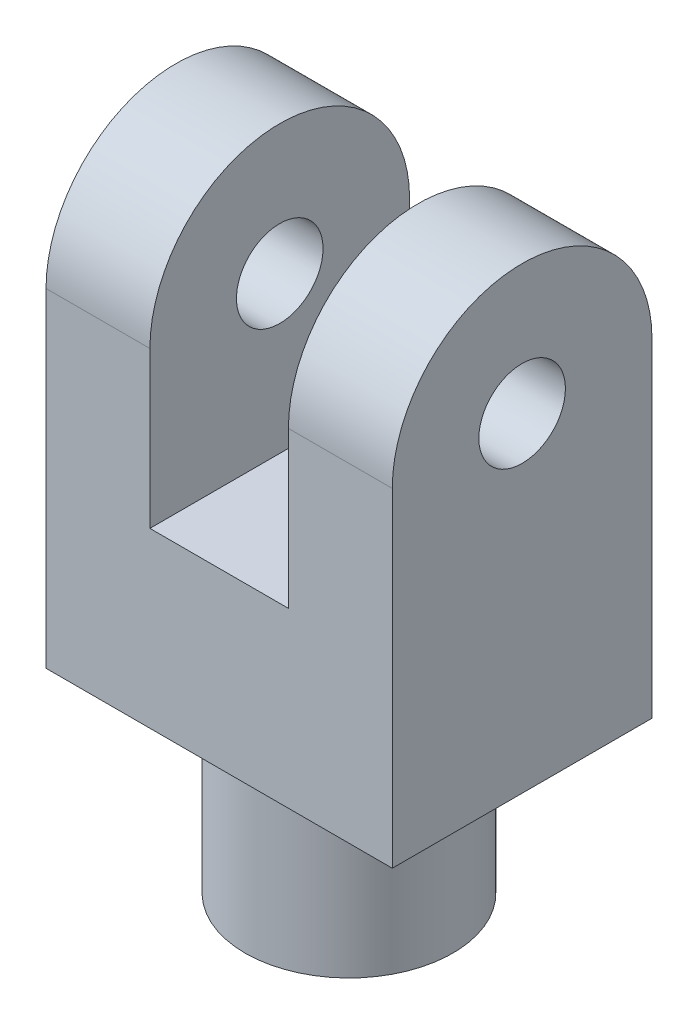
SolidWorks part; units mm, degrees
ref_plane "前视基准面" through (0, 0, 0) normal (0, 0, 1) x (1, 0, 0)
ref_plane "上视基准面" through (0, 0, 0) normal (0, 1, 0) x (1, 0, 0)
ref_plane "右视基准面" through (0, 0, 0) normal (1, 0, 0) x (0, 0, -1)
ref_plane "基准面1" through (-20, 0, 0) normal (1, 0, 0) x (0, 0, -1)
sketch "草图1" plane through (-20, 0, 0) normal (1, 0, 0) x (0, 0, -1)
  line L0 (15, 20) -> (-15, 20)
  line L1 (-15, 20) -> (-15, 58)
  line L2 (15, 58) -> (15, 20)
  arc A0 (-15, 58) -> (15, 58) centre (0, 58) cw
extrude "凸台-拉伸1" add sketch "草图1" along normal blind 40
sketch "草图2" plane through (0, 0, 0) normal (0, 1, 0) x (1, 0, 0)
  circle A0 centre (0, 0) radius 12
extrude "凸台-拉伸2" add sketch "草图2" along normal blind 20
ref_plane "基准面2" through (0, 0, -15) normal (0, 0, 1) x (1, 0, 0)
sketch "草图3" plane through (0, 0, -15) normal (0, 0, 1) x (1, 0, 0)
  line L0 (-8, 40) -> (8, 40)
  line L1 (8, 40) -> (8, 83)
  line L2 (8, 83) -> (-8, 83)
  line L3 (-8, 83) -> (-8, 40)
extrude "切除-拉伸1" cut sketch "草图3" along normal blind 30
sketch "草图4" plane through (-20, 0, 0) normal (1, 0, 0) x (0, 0, -1)
  circle A0 centre (0, 58) radius 5
extrude "切除-拉伸2" cut sketch "草图4" along normal through all
sketch "草图5" plane through (0, 0, 0) normal (0, 1, 0) x (1, 0, 0)
  circle A0 centre (0, 0) radius 6
extrude "切除-拉伸3" cut sketch "草图5" along normal blind 16
